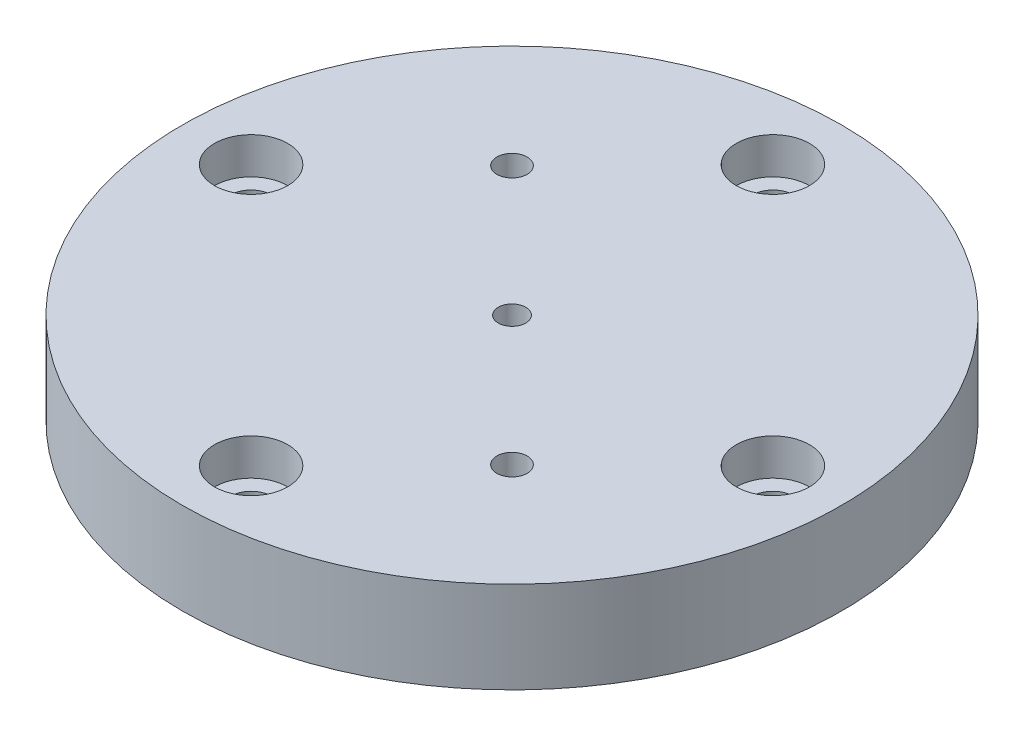
SolidWorks part; units mm, degrees
ref_plane "Front Plane" through (0, 0, 0) normal (0, 0, 1) x (1, 0, 0)
ref_plane "Top Plane" through (0, 0, 0) normal (0, 1, 0) x (1, 0, 0)
ref_plane "Right Plane" through (0, 0, 0) normal (1, 0, 0) x (0, 0, -1)
sketch "Sketch2" plane through (0, 0, 0) normal (0, 0, 1) x (1, 0, 0)
  line L0 (0, -990.2174) -> (0, 49009.7826) construction
  line L1 (0, 0) -> (32, 0)
  line L2 (32, 0) -> (32, -4)
  line L3 (32, -4) -> (36, -4)
  line L4 (36, -4) -> (36, 6)
  line L5 (36, 6) -> (0, 6)
  line L6 (0, 6) -> (0, 0)
  line L7 (55, 0) -> (-55, 0) construction
  dimension "D1" = 64
  dimension "D2" = 4
  dimension "D3" = 4
  dimension "D4" = 6
revolve "Revolve1" add sketch "Sketch2" angle 360 about L0
hole_wizard "CBORE for M4 SHCS1" positions "Sketch4" profile "Sketch3" counterbore size "M4" standard "ANSI Metric" end condition through all
sketch "Sketch4" plane through (0, 6, 0) normal (0, 1, 0) x (1, 0, 0)
  circle A0 centre (0, 0) radius 28.5 construction
  point P5 (0, 28.5)
  point P7 (-28.5, 0)
  point P9 (28.5, 0)
  point P11 (0, -28.5)
  dimension "D1" = 57
sketch "Sketch3" plane through (0, 6, -28.5) normal (1, 0, 0) x (0, 0, 1)
  line L0 (0, 0) -> (0, 10)
  line L1 (0, 10) -> (2.25, 10)
  line L3 (2.25, 10) -> (2.25, 4)
  line L4 (2.25, 4) -> (4, 4)
  line L5 (4, 4) -> (4, 0)
  line L7 (4, 0) -> (0, 0)
  line L11 (0, -6.35) -> (0, 107.95) construction
  dimension "Thru Hole Dia." = 4.5
  dimension "Thru Hole Depth" = 10
  dimension "C'Bore Dia." = 8
  dimension "C'Bore Depth" = 4
hole_wizard "M4x0.7 Tapped Hole1" positions "Sketch6" profile "Sketch5" tap size "M4x0.7" standard "ANSI Metric"
sketch "Sketch6" plane through (0, 6, 0) normal (0, 1, 0) x (1, 0, 0)
  line L0 (-14.1421, 14.1421) -> (14.1421, -14.1421) construction
  line L1 (-5.5, 0) -> (5.5, 0) construction
  point P0 (-14.1421, 14.1421)
  point P2 (14.1421, -14.1421)
  dimension "D1" = 40
  dimension "D2" = 45
sketch "Sketch5" plane through (-14.1421, 6, -14.1421) normal (1, 0, 0) x (0, 0, 1)
  line L0 (0, 0) -> (0, 9.0914)
  line L1 (0, 9.0914) -> (1.65, 8.1)
  line L2 (1.65, 8.1) -> (1.65, 0)
  line L5 (1.65, 0) -> (0, 0)
  line L10 (0, 9.0914) -> (-1.65, 8.1) construction
  line L11 (0, -6.35) -> (0, 107.95) construction
  dimension "Tap Drill Dia." = 3.3
  dimension "Tap Drill Depth" = 8.1
  dimension "Drill Angle" = 118
cosmetic thread "Hole Thread1" parameters "D1"=6, "D2"=4
cosmetic thread "Hole Thread2" parameters "D1"=6, "D2"=4
sketch "Sketch7" plane through (0, 6, 0) normal (0, 1, 0) x (1, 0, 0)
  circle A0 centre (0, 0) radius 1.5
  dimension "D1" = 3
extrude "Cut-Extrude1" cut sketch "Sketch7" against normal through all
